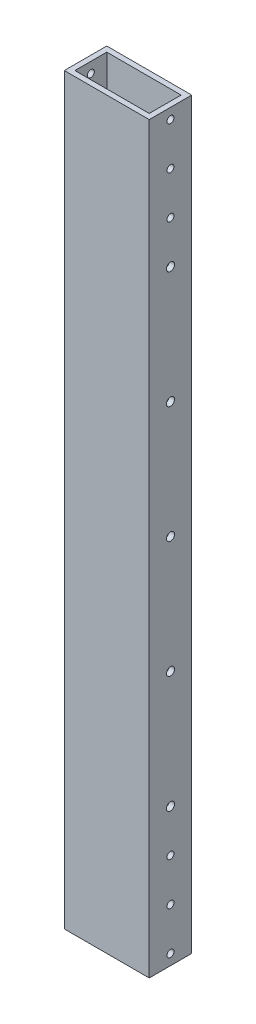
SolidWorks part; units mm, degrees
ref_plane "Front Plane" through (0, 0, 0) normal (0, 0, 1) x (1, 0, 0)
ref_plane "Top Plane" through (0, 0, 0) normal (0, 1, 0) x (1, 0, 0)
ref_plane "Right Plane" through (0, 0, 0) normal (1, 0, 0) x (0, 0, -1)
sketch "Sketch1" plane through (0, 0, 0) normal (0, 1, 0) x (1, 0, 0)
  line L0 (3.175, 3.175) -> (3.175, 22.225)
  line L1 (0, 0) -> (50.8, 0)
  line L2 (0, 0) -> (0, 25.4)
  line L3 (0, 25.4) -> (50.8, 25.4)
  line L4 (50.8, 0) -> (50.8, 25.4)
  line L5 (3.175, 22.225) -> (47.625, 22.225)
  line L6 (47.625, 3.175) -> (47.625, 22.225)
  line L7 (3.175, 3.175) -> (47.625, 3.175)
  dimension "D1" = 50.8
  dimension "D2" = 25.4
  dimension "D3" = 3.175
extrude "Boss-Extrude1" add sketch "Sketch1" along normal blind 444.5
extrude "Cut-Extrude1" cut sketch "Sketch2" against normal up to surface (50.8 mm away)
sketch "Sketch2" plane through (50.8, 398.9177, 57.2056) normal (1, 0, 0) x (0, 0, 1)
  line L0 (-82.6056, 176.6677) -> (-57.2056, 176.6677) construction
  circle A0 centre (-69.9056, -39.2323) radius 2.0828
  circle A1 centre (-69.9056, -13.8323) radius 2.0828
  circle A2 centre (-69.9056, 11.5677) radius 2.0828
  circle A3 centre (-69.9056, 341.7677) radius 2.0828
  circle A4 centre (-69.9056, 367.1677) radius 2.0828
  circle A5 centre (-69.9056, 392.5677) radius 2.0828
extrude "Cut-Extrude2" cut sketch "Sketch3" against normal up to surface (3.175 mm away)
sketch "Sketch3" plane through (50.8, 398.9177, 57.2056) normal (1, 0, 0) x (0, 0, 1)
  circle A0 centre (-69.9056, 36.9677) radius 2.4257
  circle A1 centre (-69.9056, 106.8177) radius 2.4257
  circle A2 centre (-69.9056, 176.6677) radius 2.4257
  circle A3 centre (-69.9056, 246.5177) radius 2.4257
  circle A4 centre (-69.9056, 316.3677) radius 2.4257
